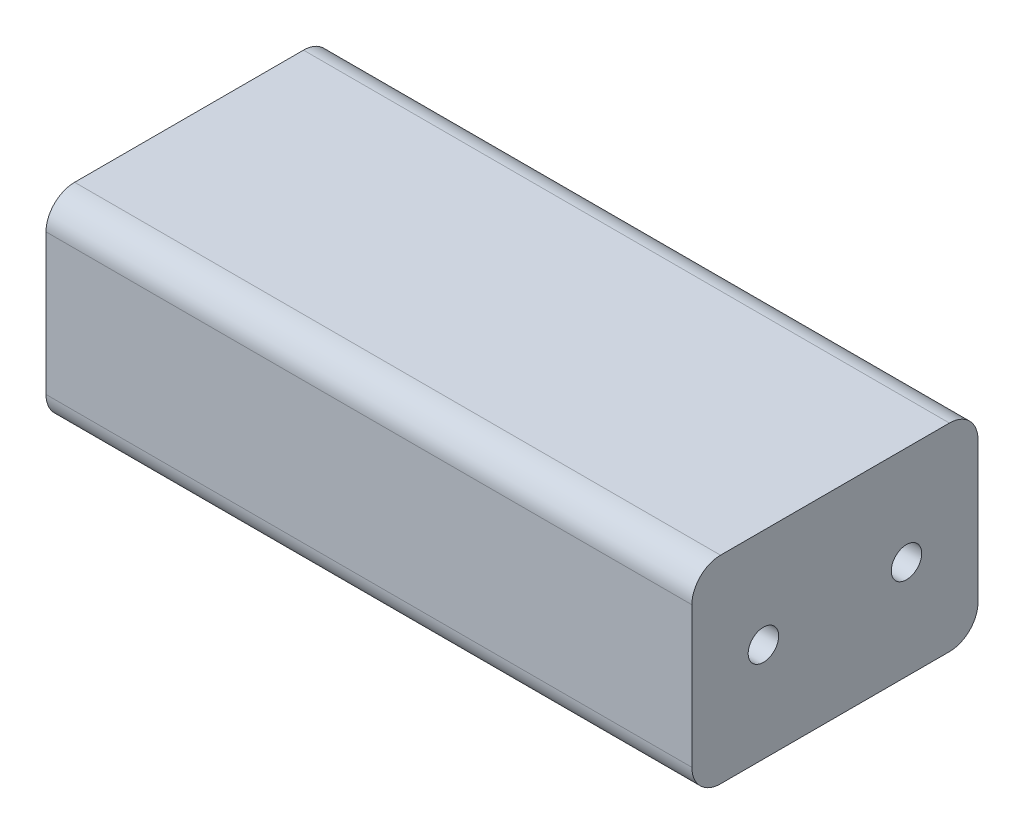
SolidWorks part; units mm, degrees
ref_plane "Front Plane" through (0, 0, 0) normal (0, 0, 1) x (1, 0, 0)
ref_plane "Top Plane" through (0, 0, 0) normal (0, 1, 0) x (1, 0, 0)
ref_plane "Right Plane" through (0, 0, 0) normal (1, 0, 0) x (0, 0, -1)
sketch "Sketch1" plane through (0, 0, 0) normal (1, 0, 0) x (0, 0, -1)
  line L1 (-12.7, 8.791) -> (12.7, 8.791)
  line L2 (-12.7, 8.791) -> (-12.7, -8.791)
  line L3 (-12.7, -8.791) -> (12.7, -8.791)
  line L4 (12.7, 8.791) -> (12.7, -8.791)
  line L5 (-12.7, 8.791) -> (12.7, -8.791) construction
  line L6 (-12.7, -8.791) -> (12.7, 8.791) construction
  point P0 (0, 0)
  dimension "D1" = 25.4
  dimension "D2" = 17.582
extrude "Boss-Extrude1" add sketch "Sketch1" along normal mid plane 57.3405
hole_wizard "#6-32 Tapped Hole1" positions "Sketch2" profile "Sketch3" tap size "#6-32" standard "ANSI Inch"
sketch "Sketch2" plane through (28.6702, 0, 0) normal (1, 0, 0) x (0, 0, -1)
  line L0 (-12.7, 8.791) -> (0, 8.791) construction
  line L1 (12.7, 8.791) -> (-12.7, 8.791) construction
  line L3 (0, 8.791) -> (0, -8.791) construction
  line L4 (-12.7, -8.791) -> (12.7, -8.791) construction
  point P0 (-6.35, 0)
  point P2 (6.35, 0)
  point P10 (-6.35, 8.791)
  point P16 (0, 0)
  point P18 (0, 0)
sketch "Sketch3" plane through (28.6702, 0, 6.35) normal (0, 1, 0) x (0, 0, -1)
  line L0 (0, 0) -> (0, 10.2107)
  line L1 (0, 10.2107) -> (1.3525, 9.398)
  line L2 (1.3525, 9.398) -> (1.3525, 0)
  line L5 (1.3525, 0) -> (0, 0)
  line L10 (0, 10.2107) -> (-1.3525, 9.398) construction
  line L11 (0, -6.35) -> (0, 107.95) construction
  dimension "Tap Drill Dia." = 2.7051
  dimension "Tap Drill Depth" = 9.398
  dimension "Drill Angle" = 118
cosmetic thread "Hole Thread3" parameters "D1"=7.0104, "D2"=3.5052
cosmetic thread "Hole Thread4" parameters "D1"=7.0104, "D2"=3.5052
mirror "Mirror1" about plane through (0, 0, 0) normal (1, 0, 0) of "#6-32 Tapped Hole1"
fillet "Fillet1" radius 2.54 4 edges at (0, -8.791, -12.7) (0, -8.791, 12.7) (0, 8.791, -12.7) (0, 8.791, 12.7)
